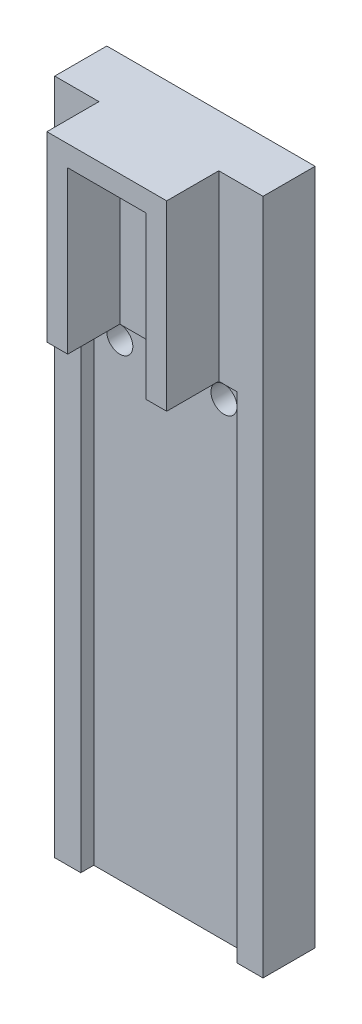
SolidWorks part; units mm, degrees
ref_plane "Front Plane" through (0, 0, 0) normal (0, 0, 1) x (1, 0, 0)
ref_plane "Top Plane" through (0, 0, 0) normal (0, 1, 0) x (1, 0, 0)
ref_plane "Right Plane" through (0, 0, 0) normal (1, 0, 0) x (0, 0, -1)
sketch "Sketch1" plane through (0, 0, 0) normal (0, 0, 1) x (1, 0, 0)
  line L1 (-12.7, -41.275) -> (12.7, -41.275)
  line L2 (-12.7, -41.275) -> (-12.7, 41.275)
  line L3 (-12.7, 41.275) -> (12.7, 41.275)
  line L4 (12.7, -41.275) -> (12.7, 41.275)
  line L5 (-12.7, -41.275) -> (12.7, 41.275) construction
  line L6 (-12.7, 41.275) -> (12.7, -41.275) construction
  point P0 (0, 0)
  dimension "D1" = 25.4
  dimension "D2" = 82.55
extrude "Boss-Extrude1" add sketch "Sketch1" along normal blind 6.35
sketch "Sketch2" plane through (0, 0, 6.35) normal (0, 0, 1) x (1, 0, 0)
  line L0 (0, 0) -> (0, -41.275) construction
  line L1 (-12.7, -41.275) -> (12.7, -41.275) construction
  line L2 (-4.7625, 15.875) -> (-4.7625, -41.275) construction
  circle A0 centre (-6.35, 15.875) radius 1.5875
  circle A1 centre (6.35, 15.875) radius 1.5875
  dimension "D1" = 3.175
  dimension "D3" = 57.15
  dimension "D2" = 4.7625
extrude "Cut-Extrude1" cut sketch "Sketch2" against normal through all
sketch "Sketch3" plane through (0, 0, 6.35) normal (0, 0, 1) x (1, 0, 0)
  line L0 (0, 0) -> (0, -41.275) construction
  line L1 (-12.7, -41.275) -> (12.7, -41.275) construction
  line L3 (-9.525, -41.275) -> (9.525, -41.275)
  line L4 (-9.525, -41.275) -> (-9.525, 19.05)
  line L5 (-9.525, 19.05) -> (9.525, 19.05)
  line L6 (9.525, -41.275) -> (9.525, 19.05)
  point P9 (0, 0)
  dimension "D1" = 19.05
  dimension "D2" = 60.325
extrude "Cut-Extrude2" cut sketch "Sketch3" against normal blind 1.5875
sketch "Sketch5" plane through (0, 0, 6.35) normal (0, 0, 1) x (1, 0, 0)
  line L0 (0, 0) -> (0, 58.437) construction
  line L2 (4.7625, 38.735) -> (-4.7625, 38.735)
  line L3 (4.7625, 38.735) -> (4.7625, 32.385)
  line L4 (4.7625, 32.385) -> (-4.7625, 32.385)
  line L5 (-4.7625, 38.735) -> (-4.7625, 32.385)
  line L6 (12.7, 41.275) -> (-12.7, 41.275) construction
  dimension "D1" = 9.525
  dimension "D2" = 6.35
  dimension "D3" = 2.54
extrude "Cut-Extrude3" cut sketch "Sketch5" against normal through all both and the other way through all
sketch "Sketch6" plane through (0, 0, 6.35) normal (0, 0, 1) x (1, 0, 0)
  line L6 (12.7, 41.275) -> (-12.7, 41.275) construction
  line L7 (-7.3025, 41.275) -> (7.3025, 41.275)
  line L8 (-7.3025, 41.275) -> (-7.3025, 19.05)
  line L9 (-7.3025, 19.05) -> (-4.7625, 19.05)
  line L10 (7.3025, 41.275) -> (7.3025, 19.05)
  line L11 (9.525, 19.05) -> (-9.525, 19.05) construction
  line L12 (4.7625, 38.735) -> (4.7625, 32.385) construction
  line L13 (-4.7625, 32.385) -> (-4.7625, 38.735) construction
  line L14 (4.7625, 38.735) -> (4.7625, 19.05)
  line L15 (-4.7625, 38.735) -> (4.7625, 38.735)
  line L16 (-4.7625, 38.735) -> (-4.7625, 19.05)
  line L17 (4.7625, 19.05) -> (7.3025, 19.05)
  dimension "D1" = 2.54
  dimension "D2" = 2.54
  dimension "D3" = 2.54
extrude "Boss-Extrude2" add sketch "Sketch6" along normal blind 6.35
